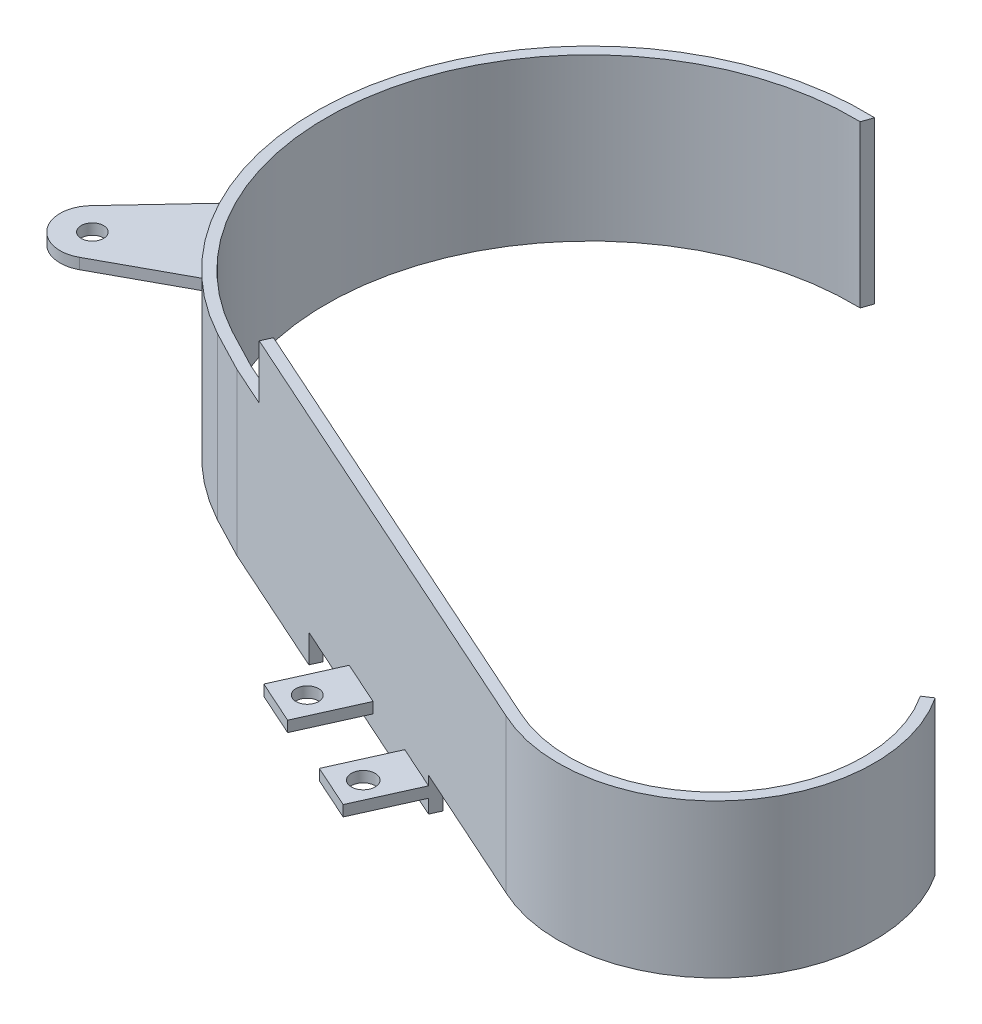
SolidWorks part; units mm, degrees
material "AISI 4130 Steel, annealed at 865C"
ref_plane "X-Y Datum" through (0, 0, 0) normal (0, 0, 1) x (1, 0, 0)
ref_plane "X-Z Datum" through (0, 0, 0) normal (0, 1, 0) x (1, 0, 0)
ref_plane "Y-Z Datum" through (0, 0, 0) normal (1, 0, 0) x (0, 0, -1)
sketch "Sketch1" plane through (0, 0, 0) normal (0, 1, 0) x (1, 0, 0)
  line L0 (131.324, -45.1056) -> (125.7387, -30.1441) construction
  line L1 (93.6073, -59.1855) -> (-43.5527, 40.713) construction
  line L2 (-43.5527, 40.713) -> (-130.5663, -18.9626) construction
  line L3 (75.1733, -98.5136) -> (-56.7825, -39.2205)
  line L4 (73.8492, -101.3994) -> (-70.3524, -36.6037)
  line L5 (75.1733, -98.5136) -> (-60.0506, -37.7519) construction
  line L6 (73.8492, -101.3994) -> (-61.352, -40.648) construction
  line L7 (-70.3524, -36.6037) -> (-82.3026, -30.3673)
  line L8 (-56.7825, -39.2205) -> (-69.0806, -33.6938)
  line L9 (-69.0806, -33.6938) -> (-80.6944, -27.6278)
  line L10 (-41.5976, 118.47) -> (-40.5107, 121.6124)
  line L11 (129.8703, -35.2793) -> (132.5211, -33.5318)
  arc A0 (76.7271, -95.7348) -> (131.324, -45.1056) centre (93.6073, -59.1855) ccw construction
  circle A1 centre (-130.5663, -18.9626) radius 3.3 construction
  circle A2 centre (-43.5527, 40.713) radius 58.7316 construction
  circle A3 centre (93.6073, -59.1855) radius 24.535 construction
  circle A4 centre (-43.5527, 40.713) radius 77.7816 construction
  arc A5 (75.1733, -98.5136) -> (129.8703, -35.2793) centre (93.6073, -59.1855) ccw
  arc A6 (75.3959, -98.6172) -> (134.2985, -43.9952) centre (93.6073, -59.1855) ccw construction
  arc A7 (-41.5976, 118.47) -> (-80.6944, -27.6278) centre (-43.5527, 40.713) ccw
  arc A8 (-40.5107, 121.6124) -> (-82.3026, -30.3673) centre (-43.5527, 40.713) ccw
  arc A9 (73.8492, -101.3994) -> (132.5211, -33.5318) centre (93.6073, -59.1855) ccw
  arc A10 (-15.3986, 116.6163) -> (-88.4132, -26.6777) centre (-43.5527, 40.713) ccw construction
  arc A11 (-16.5027, 113.6395) -> (-86.6538, -24.0347) centre (-43.5527, 40.713) ccw construction
  dimension "D3" = 117.4631
  dimension "D4" = 49.07
  dimension "D7" = 40.259
  dimension "D14" = 3.175
  dimension "D25" = 6.6
  dimension "D1" = 169.6838
  dimension "D2" = 87.0137
  dimension "D8" = 15.9701
  dimension "D9" = 32.1313
  dimension "D10" = 59.6186
  dimension "D11" = 93.6073
  dimension "D12" = 59.1855
  dimension "D13" = 105.5109
  dimension "D15" = 3.175
  dimension "D16" = 158.0904
  dimension "D17" = 81.0209
  dimension "D18" = 144.6651
  dimension "D19" = 39.3281
  dimension "D20" = 74.4068
  dimension "D21" = 13.1025
  dimension "D22" = 11.9502
  dimension "D24" = 36.263
  dimension "D5" = 19.05
  dimension "D6" = 3.175
extrude "Boss-Extrude1" add sketch "Sketch1" along normal blind 25.4 and the other way blind 38.1
ref_plane "Plane2" through (0, -6.35, 0) normal (0, -1, 0) x (-1, 0, 0)
ref_plane "Plane3" through (-26.5441, 0, 59.0733) normal (-0.4099, 0, 0.9121) x (0.9121, 0, 0.4099)
sketch "Sketch8" plane through (-26.5441, 0, 59.0733) normal (-0.4099, 0, 0.9121) x (0.9121, 0, 0.4099)
  line L5 (-6.8558, -38.5048) -> (-144.8579, -38.5048)
  line L10 (-6.8558, -38.5048) -> (-6.8558, -34.4887)
  line L11 (-35.9733, 27.2828) -> (-159.5087, 27.2828)
  line L12 (-35.9733, 27.2828) -> (-35.9733, 9.4624)
  line L13 (-35.9733, 9.4624) -> (-159.5087, 9.4624)
  line L14 (-159.5087, 27.2828) -> (-159.5087, 9.4624)
  line L15 (63.4232, -38.5048) -> (171.0719, -38.5048)
  line L16 (63.4232, -38.5048) -> (63.4232, -19.814)
  line L17 (63.4232, -19.814) -> (171.0719, -19.814)
  line L18 (171.0719, -38.5048) -> (171.0719, -19.814)
  line L19 (-6.8558, -38.5048) -> (63.4232, -38.5048)
  line L20 (-6.8558, -38.5048) -> (-6.8558, -29.7592)
  line L21 (-6.8558, -29.7592) -> (63.4232, -29.7592)
  line L22 (63.4232, -38.5048) -> (63.4232, -29.7592)
  line L23 (-6.8558, -34.4887) -> (-144.8579, -34.4887)
  line L24 (-144.8579, -38.5048) -> (-144.8579, -34.4887)
extrude "Cut-Extrude8" cut sketch "Sketch8" against normal through all contours L11 L14 L13 L12 | L15 L18 L17 L16 | L19 L20 L21 L22
sketch "Sketch9" plane through (-25.503, 0, 56.7564) normal (-0.4099, 0, 0.9121) x (0.9121, 0, 0.4099)
  line L0 (63.4232, -19.814) -> (108.9213, -19.814) construction
  line L1 (63.4232, -19.814) -> (108.9213, -19.814)
  line L2 (63.4232, -29.7592) -> (63.4232, -19.814) construction
  line L3 (63.4232, -29.7592) -> (63.4232, -19.814)
  line L4 (49.4532, -22.5248) -> (63.4232, -22.5248)
  line L6 (63.4232, -19.814) -> (63.4232, -25.6998)
  line L7 (63.4232, -25.6998) -> (49.4532, -25.6998)
  line L8 (49.4532, -22.5248) -> (49.4532, -25.6998)
  line L9 (63.4232, -22.5248) -> (63.4232, -25.6998)
  line L10 (-6.8558, -29.7592) -> (63.4232, -29.7592) construction
  line L11 (16.8576, -22.5248) -> (30.8276, -22.5248)
  line L12 (16.8576, -22.5248) -> (16.8576, -25.6998)
  line L13 (16.8576, -25.6998) -> (30.8276, -25.6998)
  line L14 (30.8276, -22.5248) -> (30.8276, -25.6998)
  dimension "D1" = 3.175
  dimension "D2" = 13.97
  dimension "D3" = 2.7108
  dimension "D4" = 3.175
  dimension "D5" = 13.97
  dimension "D6" = 32.5956
  dimension "D7" = 4.0594
extrude "Boss-Extrude2" add sketch "Sketch9" along normal blind 19.05
sketch "Sketch10" plane through (0, -25.6998, 0) normal (0, -1, 0) x (-1, 0, 0)
  line L0 (-24.5403, -100.1278) -> (-32.3483, -82.7514) construction
  line L1 (-21.2603, -90.9248) -> (8.7089, -77.4583) construction
  line L2 (-32.3483, -82.7514) -> (-19.6056, -77.0256) construction
  line L5 (31.7565, -53.9465) -> (-32.3483, -82.7514) construction
  circle A0 centre (-21.2603, -90.9248) radius 3.5
  circle A1 centre (8.7089, -77.4583) radius 3.3344
  dimension "D3" = 7
  dimension "D1" = 6.7638
  dimension "D2" = 11.9999
  dimension "D4" = 32.8558
extrude "Cut-Extrude9" cut sketch "Sketch10" against normal through all
ref_plane "Plane4" through (0, 2.3657, 0) normal (0, 1, 0) x (1, 0, 0)
sketch "Sketch11" plane through (0, 2.3657, 0) normal (0, 1, 0) x (1, 0, 0)
  line L0 (-137.5153, -12.4481) -> (-117.841, 8.5384)
  line L1 (-126.0185, -27.3317) -> (-102.6403, -14.628)
  circle A0 centre (-130.5663, -18.9626) radius 3.3 construction
  circle A1 centre (-130.5663, -18.9626) radius 3.3 construction
  circle A2 centre (-130.5663, -18.9626) radius 9.525 construction
  arc A3 (-117.841, 8.5384) -> (-102.6403, -14.628) centre (-43.5527, 40.713) ccw
  arc A4 (-40.5107, 121.6124) -> (-82.3026, -30.3673) centre (-43.5527, 40.713) ccw construction
  arc A5 (-137.5153, -12.4481) -> (-126.0185, -27.3317) centre (-130.5663, -18.9626) ccw
  circle A6 centre (-130.5663, -18.9626) radius 3.3
  dimension "D1" = 19.05
extrude "Boss-Extrude3" add sketch "Sketch11" along normal blind 3.175
sketch "Bend-Lines1" [suppressed] plane through (0, 0, 0) normal (0, 1, 0) x (1, 0, 0)
sketch "Bounding-Box1" [suppressed] plane through (0, 0, 0) normal (0, 1, 0) x (1, 0, 0)
